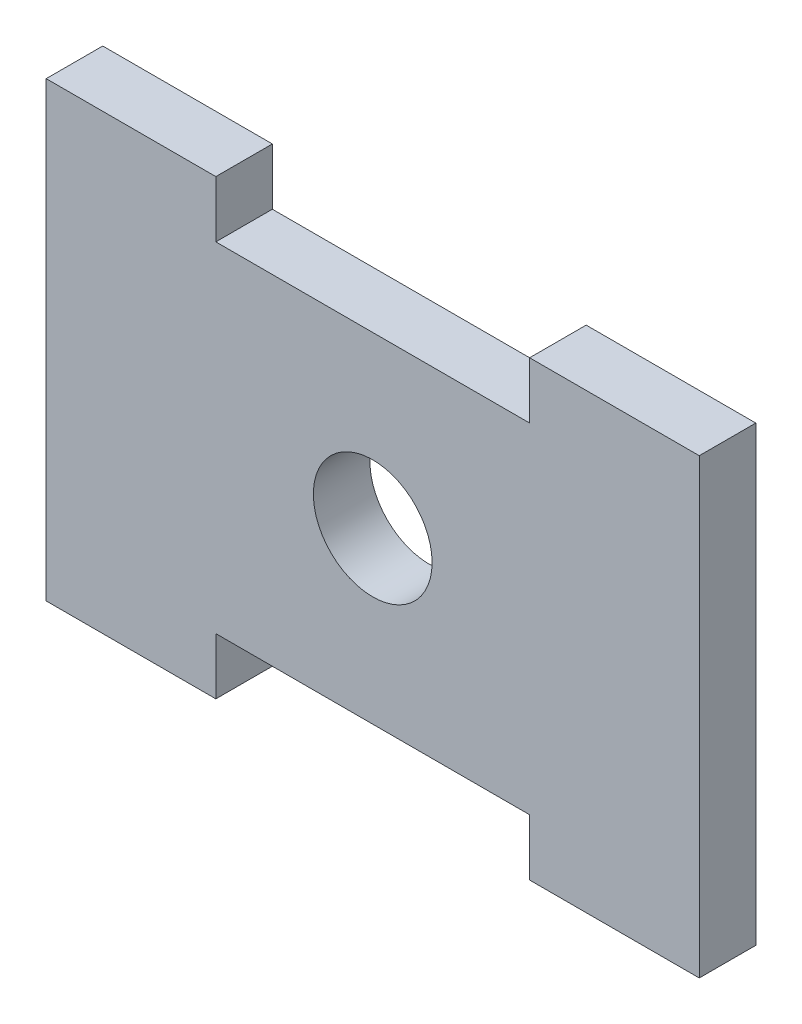
SolidWorks part; units mm, degrees
ref_plane "前视基准面" through (0, 0, 0) normal (0, 0, 1) x (1, 0, 0)
ref_plane "上视基准面" through (0, 0, 0) normal (0, 1, 0) x (1, 0, 0)
ref_plane "右视基准面" through (0, 0, 0) normal (1, 0, 0) x (0, 0, -1)
sketch "草图1" plane through (0, 0, 0) normal (0, 0, 1) x (1, 0, 0)
  line L0 (0, 0) -> (17.1, 0) construction
  line L1 (8.55, 0) -> (8.55, 1.7609) construction
  line L2 (-3, 1) -> (3, 1)
  line L3 (-3, 1) -> (-3, -1)
  line L4 (-3, -1) -> (3, -1) construction
  line L5 (3, 1) -> (3, -1)
  line L6 (-3, 1) -> (3, -1) construction
  line L7 (-3, -1) -> (3, 1) construction
  line L8 (14.1, 1) -> (14.1, -1)
  line L9 (20.1, 1) -> (20.1, -1)
  line L10 (20.1, 1) -> (14.1, 1)
  line L11 (3, -1) -> (14.1, -1)
  line L12 (-4.7034, -7) -> (23.2867, -7) construction
  line L13 (-3, -13) -> (3, -15) construction
  line L14 (-3, -15) -> (3, -13) construction
  line L15 (-3, -13) -> (3, -13) construction
  line L16 (8.55, -14) -> (8.55, -15.7609) construction
  line L17 (0, -14) -> (17.1, -14) construction
  line L18 (3, -13) -> (14.1, -13)
  line L19 (20.1, -15) -> (14.1, -15)
  line L20 (20.1, -15) -> (20.1, -13)
  line L21 (14.1, -15) -> (14.1, -13)
  line L22 (3, -15) -> (3, -13)
  line L23 (-3, -15) -> (-3, -13)
  line L24 (-3, -15) -> (3, -15)
  line L25 (-3, -13) -> (-3, -1)
  line L26 (20.1, -1) -> (20.1, -13)
  line L27 (8.55, -1) -> (8.55, -13) construction
  circle A0 centre (8.55, -7) radius 2.1
  dimension "D1" = 17.1
  dimension "D2" = 2
  dimension "D3" = 6
  dimension "D4" = 12
extrude "凸台-拉伸1" add sketch "草图1" along normal blind 2
